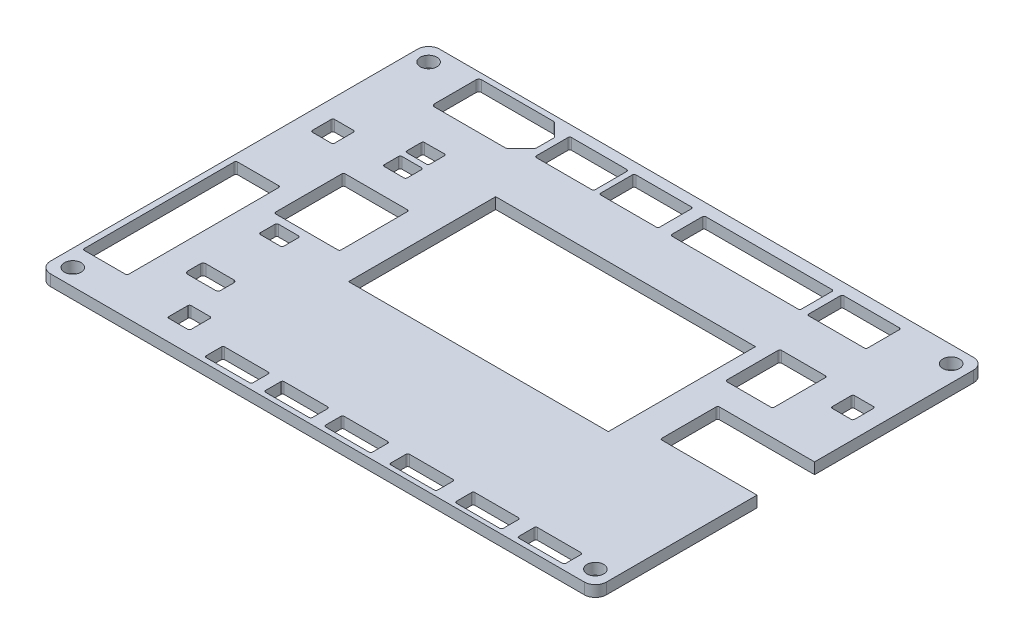
SolidWorks part; units mm, degrees
ref_plane "前视基准面" through (0, 0, 0) normal (0, 0, 1) x (1, 0, 0)
ref_plane "上视基准面" through (0, 0, 0) normal (0, 1, 0) x (1, 0, 0)
ref_plane "右视基准面" through (0, 0, 0) normal (1, 0, 0) x (0, 0, -1)
other "Configuration Table"
sketch "草图1" plane through (0, 0, 0) normal (0, 1, 0) x (1, 0, 0)
  line L0 (0, 0) -> (-50000, 0) construction
  line L1 (-48, 35) -> (48, 35)
  line L2 (-50, 33) -> (-50, -33)
  line L3 (-48, -35) -> (48, -35)
  line L4 (50, 33) -> (50, -33)
  line L5 (-50, 35) -> (50, -35) construction
  line L6 (-50, -35) -> (50, 35) construction
  line L7 (0, 0) -> (0, 50000) construction
  circle A0 centre (-47, 32) radius 1.5
  circle A1 centre (-47, -32) radius 1.5
  circle A2 centre (47, -32) radius 1.5
  circle A3 centre (47, 32) radius 1.5
  arc A4 (-48, -35) -> (-50, -33) centre (-48, -33) cw
  arc A5 (-50, 33) -> (-48, 35) centre (-48, 33) cw
  arc A6 (50, 33) -> (48, 35) centre (48, 33) ccw
  arc A7 (50, -33) -> (48, -35) centre (48, -33) cw
  point P0 (0, 0)
  dimension "D3" = 3
  dimension "D4" = 3
  dimension "D5" = 2
  dimension "D1" = 100
  dimension "D2" = 70
extrude "凸台-拉伸1" add sketch "草图1" along normal blind 2
sketch "草图2" plane through (0, 2, 0) normal (0, 1, 0) x (1, 0, 0)
  line L0 (-39.4687, 34) -> (-26.524, 34)
  line L1 (-46.5201, 14.6058) -> (-43.1201, 14.6058)
  line L2 (-46.8201, 14.3058) -> (-46.8201, 10.9058)
  line L3 (-46.5201, 10.6058) -> (-43.1201, 10.6058)
  line L4 (-42.8201, 14.3058) -> (-42.8201, 10.9058)
  line L5 (-46.8201, 14.6058) -> (-42.8201, 10.6058) construction
  line L6 (-46.8201, 10.6058) -> (-42.8201, 14.6058) construction
  line L7 (-30.4169, -27.3038) -> (-27.0169, -27.3038)
  line L8 (-30.7169, -27.6038) -> (-30.7169, -31.0038)
  line L9 (-30.4169, -31.3038) -> (-27.0169, -31.3038)
  line L10 (-26.7169, -27.6038) -> (-26.7169, -31.0038)
  line L11 (-30.7169, -27.3038) -> (-26.7169, -31.3038) construction
  line L12 (-30.7169, -31.3038) -> (-26.7169, -27.3038) construction
  line L13 (43.2758, 18.3426) -> (46.6758, 18.3426)
  line L14 (42.9758, 18.0426) -> (42.9758, 14.6426)
  line L15 (43.2758, 14.3426) -> (46.6758, 14.3426)
  line L16 (46.9758, 18.0426) -> (46.9758, 14.6426)
  line L17 (42.9758, 18.3426) -> (46.9758, 14.3426) construction
  line L18 (42.9758, 14.3426) -> (46.9758, 18.3426) construction
  line L20 (-48.9193, -14.8193) -> (-48.9193, -28.0193)
  line L21 (-48.6193, -28.3193) -> (-41.2193, -28.3193)
  line L22 (-40.9193, -14.8193) -> (-40.9193, -28.0193)
  line L23 (-48.9193, -14.8193) -> (-40.9193, -28.3193) construction
  line L24 (-48.9193, -28.3193) -> (-40.9193, -14.8193) construction
  line L27 (48, 35) -> (-48, 35) construction
  line L28 (-26.1704, 33.8536) -> (-24.0546, 31.7377)
  line L29 (-23.9081, 31.3842) -> (-23.9081, 28.3563)
  line L30 (-24.0546, 28.0028) -> (-26.3851, 25.6723)
  line L31 (-26.7386, 25.5258) -> (-39.4687, 25.5258)
  line L32 (-39.9687, 26.0258) -> (-39.9687, 33.5)
  line L33 (-22.4062, 33.091) -> (-12.4321, 33.091)
  line L34 (-12.1321, 32.791) -> (-12.1321, 27.091)
  line L35 (-12.4321, 26.791) -> (-22.4062, 26.791)
  line L36 (-22.7062, 27.091) -> (-22.7062, 32.791)
  line L37 (-12.5321, 32.791) -> (-22.3321, 32.791) construction
  line L38 (-12.4321, 28.691) -> (-12.4321, 32.691) construction
  line L39 (-14.6321, 27.091) -> (-12.5321, 27.091) construction
  line L40 (-10.7988, 33.0656) -> (-0.7988, 33.0656)
  line L41 (-0.4988, 32.7656) -> (-0.4988, 27.0656)
  line L42 (-0.7988, 26.7656) -> (-10.7988, 26.7656)
  line L43 (-11.0988, 27.0656) -> (-11.0988, 32.7656)
  line L45 (-0.8988, 32.7656) -> (-10.6988, 32.7656) construction
  line L46 (-10.7988, 32.6656) -> (-10.7988, 28.6656) construction
  line L47 (-0.7988, 28.6656) -> (-0.7988, 32.6656) construction
  line L48 (-2.9988, 27.0656) -> (-0.8988, 27.0656) construction
  line L49 (26.7362, 32.941) -> (36.7362, 32.941)
  line L50 (37.0362, 32.641) -> (37.0362, 26.941)
  line L51 (36.7362, 26.641) -> (26.7362, 26.641)
  line L52 (26.4362, 26.941) -> (26.4362, 32.641)
  line L53 (29.6457, 18.8199) -> (37.5537, 18.8199)
  line L54 (33.5362, 32.641) -> (29.9362, 32.641) construction
  line L55 (36.7362, 27.041) -> (36.7362, 31.041) construction
  line L56 (26.8362, 26.941) -> (36.6362, 26.941) construction
  line L57 (26.7362, 31.041) -> (26.7362, 27.041) construction
  line L58 (-48.9193, -14.8193) -> (-48.9193, -1.0477)
  line L59 (-48.6193, -0.7477) -> (-41.2193, -0.7477)
  line L60 (-40.9193, -1.0477) -> (-40.9193, -14.8193)
  line L61 (-41.6894, -1.0477) -> (-48.0894, -1.0477) construction
  line L62 (-35.6094, -19.4542) -> (-30.6109, -19.4542)
  line L63 (-30.1109, -19.9558) -> (-30.1179, -22.2466)
  line L64 (-30.6171, -22.7451) -> (-35.6086, -22.7534)
  line L65 (-36.1094, -22.2534) -> (-36.1094, -19.9542)
  line L66 (-34.8288, 19.0935) -> (-31.2753, 19.1197)
  line L67 (-30.973, 18.8197) -> (-30.973, 16.1942)
  line L68 (-31.2753, 15.8942) -> (-34.8288, 15.9204)
  line L69 (-35.1266, 16.2204) -> (-35.1266, 18.7935)
  line L70 (-30.8725, 12.0316) -> (-30.8725, 14.6003)
  line L71 (-31.1725, 14.9003) -> (-34.6996, 14.9003)
  line L72 (-34.9996, 14.6003) -> (-34.9996, 12.0316)
  line L73 (-34.6996, 11.7316) -> (-31.1725, 11.7316)
  line L74 (-37.089, 7.0841) -> (-25.9012, 7.0841)
  line L75 (-25.6012, 6.7841) -> (-25.6012, -5.128)
  line L76 (-25.9012, -5.428) -> (-30.1778, -5.428)
  line L77 (-31.3355, -7.0684) -> (-31.3355, -9.7188)
  line L78 (-31.6355, -10.0188) -> (-35.2473, -10.0188)
  line L80 (-13.7409, -31.1189) -> (-15.2809, -31.1189) construction
  line L81 (-19.9904, 17.0582) -> (26.7362, 17.0582)
  line L82 (-19.9904, 17.0582) -> (-19.9904, -9.4111)
  line L83 (-19.9904, -9.4111) -> (26.7362, -9.4111)
  line L84 (26.7362, 17.0582) -> (26.7362, -9.4111)
  line L85 (-20.9609, -30.7189) -> (-13.1309, -30.7189)
  line L86 (-21.2609, -31.0189) -> (-21.2609, -33.7589)
  line L87 (-20.9609, -34.0589) -> (-13.1309, -34.0589)
  line L88 (-12.8309, -31.0189) -> (-12.8309, -33.7589)
  line L89 (-15.2809, -33.6589) -> (-13.7409, -33.6589) construction
  line L90 (-20.8609, -31.7189) -> (-20.8609, -33.0589) construction
  line L91 (-2.0761, -31.0815) -> (-2.0761, -33.8215)
  line L92 (-10.5061, -31.0815) -> (-10.5061, -33.8215)
  line L93 (-10.2061, -30.7815) -> (-2.3761, -30.7815)
  line L94 (-10.2061, -34.1215) -> (-2.3761, -34.1215)
  line L95 (8.719, -31.0815) -> (8.719, -33.8215)
  line L96 (0.589, -30.7815) -> (8.419, -30.7815)
  line L97 (0.289, -31.0815) -> (0.289, -33.8215)
  line L98 (0.589, -34.1215) -> (8.419, -34.1215)
  line L99 (12.3639, -30.8204) -> (20.1939, -30.8204)
  line L100 (20.4939, -31.1204) -> (20.4939, -33.8604)
  line L101 (12.3639, -34.1604) -> (20.1939, -34.1604)
  line L102 (12.0639, -31.1204) -> (12.0639, -33.8604)
  line L103 (23.9258, -31.1966) -> (23.9258, -33.9366)
  line L104 (24.2258, -34.2366) -> (32.0558, -34.2366)
  line L105 (24.2258, -30.8966) -> (32.0558, -30.8966)
  line L106 (32.3558, -31.1966) -> (32.3558, -33.9366)
  line L107 (43.4302, -31.0188) -> (43.4302, -33.7588)
  line L108 (35.3002, -30.7188) -> (43.1302, -30.7188)
  line L109 (35.3002, -34.0588) -> (43.1302, -34.0588)
  line L110 (35.0002, -31.0188) -> (35.0002, -33.7588)
  line L111 (50, -33) -> (50, 33) construction
  line L112 (32.8812, 4.4238) -> (50, 4.4238)
  line L113 (32.5812, 4.1238) -> (32.5812, -5.6249)
  line L114 (32.8812, -5.9249) -> (50, -5.9249)
  line L115 (50, 4.4238) -> (50, -5.9249)
  line L116 (11.7771, 32.5365) -> (10.0371, 32.5365) construction
  line L117 (2.0171, 32.8365) -> (24.7191, 32.8365)
  line L118 (1.7171, 32.5365) -> (1.7171, 27.0521)
  line L119 (2.0171, 26.7521) -> (24.7191, 26.7521)
  line L120 (25.0191, 32.5365) -> (25.0191, 27.0521)
  line L121 (2.0171, 31.9365) -> (2.0171, 30.4765) construction
  line L122 (9.9184, 27.0521) -> (11.8957, 27.0521) construction
  line L123 (24.7191, 27.4742) -> (24.7191, 28.9342) construction
  line L124 (-30.1778, -5.428) -> (-37.089, -5.428)
  line L125 (-37.389, -5.128) -> (-37.389, 6.7841)
  line L126 (-35.5473, -9.7188) -> (-35.5473, -7.0684)
  line L127 (-35.2473, -6.7684) -> (-31.6355, -6.7684)
  line L128 (29.3457, 18.5199) -> (29.3457, 9.3179)
  line L129 (29.6457, 9.0179) -> (37.5537, 9.0179)
  line L130 (37.8537, 18.5199) -> (37.8537, 9.3179)
  arc A0 (-35.6086, -22.7534) -> (-36.1094, -22.2534) centre (-35.6094, -22.2534) cw
  arc A3 (-39.4687, 34) -> (-39.9687, 33.5) centre (-39.4687, 33.5) ccw
  arc A4 (-39.9687, 26.0258) -> (-39.4687, 25.5258) centre (-39.4687, 26.0258) ccw
  arc A5 (-26.3851, 25.6723) -> (-26.7386, 25.5258) centre (-26.7386, 26.0258) cw
  arc A6 (-23.9081, 28.3563) -> (-24.0546, 28.0028) centre (-24.4081, 28.3563) cw
  arc A7 (-23.9081, 31.3842) -> (-24.0546, 31.7377) centre (-24.4081, 31.3842) ccw
  arc A8 (-26.1704, 33.8536) -> (-26.524, 34) centre (-26.524, 33.5) ccw
  arc A9 (-30.1179, -22.2466) -> (-30.6171, -22.7451) centre (-30.6179, -22.2451) cw
  arc A10 (-30.6109, -19.4542) -> (-30.1109, -19.9558) centre (-30.6109, -19.9542) cw
  arc A11 (-35.6094, -19.4542) -> (-36.1094, -19.9542) centre (-35.6094, -19.9542) ccw
  arc A12 (-27.0169, -27.3038) -> (-26.7169, -27.6038) centre (-27.0169, -27.6038) cw
  arc A13 (-30.7169, -31.0038) -> (-30.4169, -31.3038) centre (-30.4169, -31.0038) ccw
  arc A14 (-30.4169, -27.3038) -> (-30.7169, -27.6038) centre (-30.4169, -27.6038) ccw
  arc A15 (-27.0169, -31.3038) -> (-26.7169, -31.0038) centre (-27.0169, -31.0038) ccw
  arc A16 (-48.9193, -28.0193) -> (-48.6193, -28.3193) centre (-48.6193, -28.0193) ccw
  arc A17 (-41.2193, -28.3193) -> (-40.9193, -28.0193) centre (-41.2193, -28.0193) ccw
  arc A18 (-48.9193, -1.0477) -> (-48.6193, -0.7477) centre (-48.6193, -1.0477) cw
  arc A19 (-41.2193, -0.7477) -> (-40.9193, -1.0477) centre (-41.2193, -1.0477) cw
  arc A20 (46.6758, 18.3426) -> (46.9758, 18.0426) centre (46.6758, 18.0426) cw
  arc A21 (42.9758, 14.6426) -> (43.2758, 14.3426) centre (43.2758, 14.6426) ccw
  arc A22 (43.2758, 18.3426) -> (42.9758, 18.0426) centre (43.2758, 18.0426) ccw
  arc A23 (46.6758, 14.3426) -> (46.9758, 14.6426) centre (46.6758, 14.6426) ccw
  arc A24 (-43.1201, 14.6058) -> (-42.8201, 14.3058) centre (-43.1201, 14.3058) cw
  arc A25 (-46.8201, 10.9058) -> (-46.5201, 10.6058) centre (-46.5201, 10.9058) ccw
  arc A26 (-46.5201, 14.6058) -> (-46.8201, 14.3058) centre (-46.5201, 14.3058) ccw
  arc A27 (-43.1201, 10.6058) -> (-42.8201, 10.9058) centre (-43.1201, 10.9058) ccw
  arc A28 (26.7362, 26.641) -> (26.4362, 26.941) centre (26.7362, 26.941) cw
  arc A29 (37.0362, 26.941) -> (36.7362, 26.641) centre (36.7362, 26.941) cw
  arc A30 (36.7362, 32.941) -> (37.0362, 32.641) centre (36.7362, 32.641) cw
  arc A31 (26.7362, 32.941) -> (26.4362, 32.641) centre (26.7362, 32.641) ccw
  arc A32 (-10.7988, 26.7656) -> (-11.0988, 27.0656) centre (-10.7988, 27.0656) cw
  arc A33 (-0.4988, 27.0656) -> (-0.7988, 26.7656) centre (-0.7988, 27.0656) cw
  arc A34 (-0.7988, 33.0656) -> (-0.4988, 32.7656) centre (-0.7988, 32.7656) cw
  arc A35 (-10.7988, 33.0656) -> (-11.0988, 32.7656) centre (-10.7988, 32.7656) ccw
  arc A36 (-22.4062, 26.791) -> (-22.7062, 27.091) centre (-22.4062, 27.091) cw
  arc A37 (-12.1321, 27.091) -> (-12.4321, 26.791) centre (-12.4321, 27.091) cw
  arc A38 (-12.4321, 33.091) -> (-12.1321, 32.791) centre (-12.4321, 32.791) cw
  arc A39 (-22.4062, 33.091) -> (-22.7062, 32.791) centre (-22.4062, 32.791) ccw
  arc A40 (-13.1309, -30.7189) -> (-12.8309, -31.0189) centre (-13.1309, -31.0189) cw
  arc A41 (-21.2609, -33.7589) -> (-20.9609, -34.0589) centre (-20.9609, -33.7589) ccw
  arc A42 (-13.1309, -34.0589) -> (-12.8309, -33.7589) centre (-13.1309, -33.7589) ccw
  arc A43 (-20.9609, -30.7189) -> (-21.2609, -31.0189) centre (-20.9609, -31.0189) ccw
  arc A44 (-10.5061, -33.8215) -> (-10.2061, -34.1215) centre (-10.2061, -33.8215) ccw
  arc A45 (-10.2061, -30.7815) -> (-10.5061, -31.0815) centre (-10.2061, -31.0815) ccw
  arc A46 (-2.3761, -34.1215) -> (-2.0761, -33.8215) centre (-2.3761, -33.8215) ccw
  arc A47 (-2.3761, -30.7815) -> (-2.0761, -31.0815) centre (-2.3761, -31.0815) cw
  arc A48 (0.289, -33.8215) -> (0.589, -34.1215) centre (0.589, -33.8215) ccw
  arc A49 (8.419, -34.1215) -> (8.719, -33.8215) centre (8.419, -33.8215) ccw
  arc A50 (8.419, -30.7815) -> (8.719, -31.0815) centre (8.419, -31.0815) cw
  arc A51 (0.589, -30.7815) -> (0.289, -31.0815) centre (0.589, -31.0815) ccw
  arc A52 (12.0639, -33.8604) -> (12.3639, -34.1604) centre (12.3639, -33.8604) ccw
  arc A53 (20.1939, -30.8204) -> (20.4939, -31.1204) centre (20.1939, -31.1204) cw
  arc A54 (12.3639, -30.8204) -> (12.0639, -31.1204) centre (12.3639, -31.1204) ccw
  arc A55 (20.1939, -34.1604) -> (20.4939, -33.8604) centre (20.1939, -33.8604) ccw
  arc A56 (23.9258, -33.9366) -> (24.2258, -34.2366) centre (24.2258, -33.9366) ccw
  arc A57 (32.0558, -30.8966) -> (32.3558, -31.1966) centre (32.0558, -31.1966) cw
  arc A58 (24.2258, -30.8966) -> (23.9258, -31.1966) centre (24.2258, -31.1966) ccw
  arc A59 (32.0558, -34.2366) -> (32.3558, -33.9366) centre (32.0558, -33.9366) ccw
  arc A60 (43.1302, -34.0588) -> (43.4302, -33.7588) centre (43.1302, -33.7588) ccw
  arc A61 (35.3002, -30.7188) -> (35.0002, -31.0188) centre (35.3002, -31.0188) ccw
  arc A62 (35.0002, -33.7588) -> (35.3002, -34.0588) centre (35.3002, -33.7588) ccw
  arc A63 (43.1302, -30.7188) -> (43.4302, -31.0188) centre (43.1302, -31.0188) cw
  arc A64 (-34.6996, 14.9003) -> (-34.9996, 14.6003) centre (-34.6996, 14.6003) ccw
  arc A65 (-34.9996, 12.0316) -> (-34.6996, 11.7316) centre (-34.6996, 12.0316) ccw
  arc A66 (-30.8725, 14.6003) -> (-31.1725, 14.9003) centre (-31.1725, 14.6003) ccw
  arc A67 (-30.8725, 12.0316) -> (-31.1725, 11.7316) centre (-31.1725, 12.0316) cw
  arc A68 (-34.8288, 15.9204) -> (-35.1266, 16.2204) centre (-34.8266, 16.2204) cw
  arc A69 (-30.973, 16.1942) -> (-31.2753, 15.8942) centre (-31.273, 16.1942) cw
  arc A70 (-31.2753, 19.1197) -> (-30.973, 18.8197) centre (-31.273, 18.8197) cw
  arc A71 (-34.8288, 19.0935) -> (-35.1266, 18.7935) centre (-34.8266, 18.7935) ccw
  arc A72 (-35.2473, -10.0188) -> (-35.5473, -9.7188) centre (-35.2473, -9.7188) cw
  arc A73 (-31.3355, -9.7188) -> (-31.6355, -10.0188) centre (-31.6355, -9.7188) cw
  arc A75 (-25.6012, -5.128) -> (-25.9012, -5.428) centre (-25.9012, -5.128) cw
  arc A76 (-25.9012, 7.0841) -> (-25.6012, 6.7841) centre (-25.9012, 6.7841) cw
  arc A77 (-37.089, 7.0841) -> (-37.389, 6.7841) centre (-37.089, 6.7841) ccw
  arc A78 (24.7191, 32.8365) -> (25.0191, 32.5365) centre (24.7191, 32.5365) cw
  arc A79 (1.7171, 27.0521) -> (2.0171, 26.7521) centre (2.0171, 27.0521) ccw
  arc A80 (24.7191, 26.7521) -> (25.0191, 27.0521) centre (24.7191, 27.0521) ccw
  arc A81 (2.0171, 32.8365) -> (1.7171, 32.5365) centre (2.0171, 32.5365) ccw
  arc A82 (-31.6355, -6.7684) -> (-31.3355, -7.0684) centre (-31.6355, -7.0684) cw
  arc A83 (-35.5473, -7.0684) -> (-35.2473, -6.7684) centre (-35.2473, -7.0684) cw
  arc A84 (-37.089, -5.428) -> (-37.389, -5.128) centre (-37.089, -5.128) cw
  arc A85 (32.5812, -5.6249) -> (32.8812, -5.9249) centre (32.8812, -5.6249) ccw
  arc A86 (32.8812, 4.4238) -> (32.5812, 4.1238) centre (32.8812, 4.1238) ccw
  arc A87 (37.5537, 18.8199) -> (37.8537, 18.5199) centre (37.5537, 18.5199) cw
  arc A88 (29.3457, 9.3179) -> (29.6457, 9.0179) centre (29.6457, 9.3179) ccw
  arc A89 (37.5537, 9.0179) -> (37.8537, 9.3179) centre (37.5537, 9.3179) ccw
  arc A90 (29.6457, 18.8199) -> (29.3457, 18.5199) centre (29.6457, 18.5199) ccw
  point P0 (-44.8201, 12.6058)
  point P5 (-28.7169, -29.3038)
  point P10 (44.9758, 16.3426)
  point P15 (-44.9193, -21.5693)
  point P290 (-34.9996, 14.9003)
  point P293 (-34.9996, 11.7316)
  point P296 (-30.8725, 14.9003)
  point P299 (-30.8725, 11.7316)
  point P302 (-35.1266, 15.9226)
  point P305 (-30.973, 15.892)
  point P308 (-30.973, 19.122)
  point P311 (-35.1266, 19.0913)
  point P343 (32.5812, 4.4238)
  dimension "D9" = 0.5
  dimension "D10" = 0.5
  dimension "D11" = 0.5
  dimension "D12" = 0.5
  dimension "D13" = 0.5
  dimension "D14" = 0.5
  dimension "D28" = 0.5
  dimension "D29" = 0.5
  dimension "D30" = 0.5
  dimension "D31" = 0.5
  dimension "D32" = 0.3
  dimension "D33" = 0.3
  dimension "D34" = 0.3
  dimension "D35" = 0.3
  dimension "D36" = 0.3
  dimension "D37" = 0.3
  dimension "D38" = 0.3
  dimension "D39" = 0.3
  dimension "D40" = 0.3
  dimension "D41" = 0.3
  dimension "D42" = 0.3
  dimension "D43" = 0.3
  dimension "D44" = 0.3
  dimension "D45" = 0.3
  dimension "D46" = 0.3
  dimension "D47" = 0.3
  dimension "D48" = 0.3
  dimension "D49" = 0.3
  dimension "D50" = 0.3
  dimension "D51" = 0.3
  dimension "D52" = 0.3
  dimension "D53" = 0.3
  dimension "D54" = 0.3
  dimension "D55" = 0.3
  dimension "D56" = 0.3
  dimension "D57" = 0.3
  dimension "D58" = 0.3
  dimension "D59" = 0.3
  dimension "D64" = 0.3
  dimension "D65" = 0.3
  dimension "D66" = 0.3
  dimension "D67" = 0.3
  dimension "D68" = 0.3
  dimension "D69" = 0.3
  dimension "D70" = 0.3
  dimension "D71" = 0.3
  dimension "D72" = 0.3
  dimension "D73" = 0.3
  dimension "D74" = 0.3
  dimension "D75" = 0.3
  dimension "D76" = 0.3
  dimension "D77" = 0.3
  dimension "D78" = 0.3
  dimension "D79" = 0.3
  dimension "D80" = 0.3
  dimension "D81" = 0.3
  dimension "D82" = 0.3
  dimension "D83" = 0.3
  dimension "D84" = 0.3
  dimension "D85" = 0.3
  dimension "D86" = 0.3
  dimension "D87" = 0.3
  dimension "D92" = 0.3
  dimension "D93" = 0.3
  dimension "D94" = 0.3
  dimension "D95" = 0.3
  dimension "D96" = 0.3
  dimension "D97" = 0.3
  dimension "D98" = 0.3
  dimension "D99" = 0.3
  dimension "D100" = 0.3
  dimension "D101" = 0.3
  dimension "D102" = 0.3
  dimension "D103" = 0.3
  dimension "D104" = 0.3
  dimension "D105" = 0.3
  dimension "D106" = 0.3
  dimension "D107" = 0.3
  dimension "D108" = 0.3
  dimension "D109" = 0.3
  dimension "D110" = 0.3
  dimension "D111" = 0.3
  dimension "D112" = 0.3
  dimension "D113" = 0.3
  dimension "D114" = 0.3
  dimension "D115" = 0.3
  dimension "D116" = 0.3
  dimension "D117" = 0.3
  dimension "D1" = 4
  dimension "D2" = 4
  dimension "D3" = 4
  dimension "D4" = 4
  dimension "D5" = 4
  dimension "D6" = 4
  dimension "D7" = 13.5
  dimension "D8" = 8
  dimension "D15" = 1
  dimension "D16" = 0.3
  dimension "D17" = 0.3
  dimension "D18" = 0.3
  dimension "D19" = 0.3
  dimension "D20" = 0.3
  dimension "D21" = 0.3
  dimension "D22" = 0.3
  dimension "D23" = 0.3
  dimension "D24" = 0.3
  dimension "D25" = 0.3
  dimension "D26" = 0.3
  dimension "D27" = 0.3
  dimension "D60" = 0.4
  dimension "D61" = 0.4
  dimension "D62" = 0.4
  dimension "D63" = 0.4
  dimension "D88" = 0.3
  dimension "D89" = 0.3
  dimension "D90" = 0.3
  dimension "D91" = 0.3
extrude "切除-拉伸1" cut sketch "草图2" against normal blind 2
